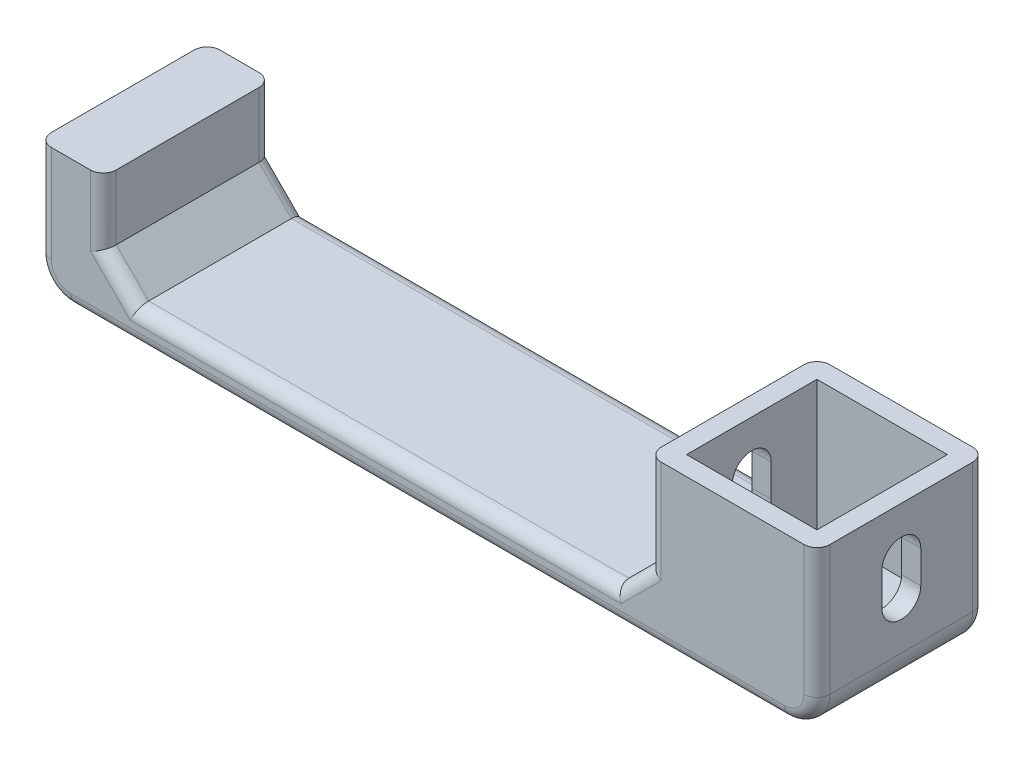
SolidWorks part; units mm, degrees
ref_plane "Front Plane" through (0, 0, 0) normal (0, 0, 1) x (1, 0, 0)
ref_plane "Top Plane" through (0, 0, 0) normal (0, 1, 0) x (1, 0, 0)
ref_plane "Right Plane" through (0, 0, 0) normal (1, 0, 0) x (0, 0, -1)
sketch "Sketch1" plane through (0, 0, 0) normal (0, 1, 0) x (1, 0, 0)
  line L1 (60, -13) -> (-60, -13)
  line L2 (60, -13) -> (60, 13)
  line L3 (60, 13) -> (-60, 13)
  line L4 (-60, -13) -> (-60, 13)
  line L5 (60, -13) -> (-60, 13) construction
  line L6 (60, 13) -> (-60, -13) construction
  point P0 (0, 0)
  dimension "D1" = 26
  dimension "D2" = 120
extrude "Boss-Extrude1" add sketch "Sketch1" along normal blind 25
sketch "Sketch3" plane through (0, 25, 0) normal (0, 1, 0) x (1, 0, 0)
  line L0 (60, 13) -> (-60, 13) construction
  line L1 (-50, 13) -> (34, 13)
  line L2 (-50, 13) -> (-50, -13)
  line L3 (-50, -13) -> (34, -13)
  line L4 (34, 13) -> (34, -13)
  line L5 (-60, -13) -> (60, -13) construction
  line L6 (60, -13) -> (60, 13) construction
  line L7 (-60, 13) -> (-60, -13) construction
  dimension "D1" = 26
  dimension "D2" = 10
extrude "Cut-Extrude1" cut sketch "Sketch3" against normal blind 20
sketch "Sketch4" plane through (0, 25, 0) normal (0, 1, 0) x (1, 0, 0)
  line L0 (-60, -13) -> (-50, -13) construction
  line L1 (-60, 13) -> (-50, 13)
  line L2 (-60, 13) -> (-60, -13)
  line L3 (-60, -13) -> (-50, -13)
  line L4 (-50, 13) -> (-50, -13)
  line L5 (-50, -13) -> (34, -13) construction
extrude "Cut-Extrude2" cut sketch "Sketch4" against normal blind 5
chamfer "Chamfer1" distance 5 angle 45 2 edges at (-50, 5, 0) (34, 5, 0)
sketch "Sketch5" plane through (0, 25, 0) normal (0, 1, 0) x (1, 0, 0)
  line L0 (60, 13) -> (34, 13) construction
  line L1 (36.95, 10.05) -> (57.05, 10.05)
  line L2 (36.95, 10.05) -> (36.95, -10.05)
  line L3 (36.95, -10.05) -> (57.05, -10.05)
  line L4 (57.05, 10.05) -> (57.05, -10.05)
  line L5 (34, -13) -> (60, -13) construction
  line L6 (60, -13) -> (60, 13) construction
  line L7 (34, 13) -> (34, -13) construction
  dimension "D1" = 2.95
  dimension "D2" = 2.95
  dimension "D3" = 2.95
  dimension "D4" = 2.95
extrude "Cut-Extrude3" cut sketch "Sketch5" against normal blind 20
fillet "Fillet1" radius 5 2 edges at (60, 0, 0) (-60, 0, 0)
fillet "Fillet2" radius 2 20 edges at (-60, 12.5, 13) (-58.5355, 1.4645, 13) (60, 15, 13) (58.5355, 1.4645, 13) (60, 15, -13) (58.5355, 1.4645, -13) (-60, 12.5, -13) (-58.5355, 1.4645, -13) (-8, 5, -13) (-47.5, 7.5, -13) (-50, 15, -13) (-50, 15, 13) (-47.5, 7.5, 13) (-8, 5, 13) (31.5, 7.5, 13) (31.5, 7.5, -13) (34, 17.5, 13) (34, 17.5, -13) (0, 0, 13) (0, 0, -13)
sketch "Sketch6" plane through (60, 0, 0) normal (1, 0, 0) x (0, 0, -1)
  line L0 (0, 17.5) -> (0, 12.5) construction
  line L1 (3, 17.5) -> (3, 12.5)
  line L2 (-3, 17.5) -> (-3, 12.5)
  line L3 (13, 25) -> (13, 5) construction
  line L4 (-11, 25) -> (11, 25) construction
  arc A0 (3, 17.5) -> (-3, 17.5) centre (0, 17.5) ccw
  arc A1 (-3, 12.5) -> (3, 12.5) centre (0, 12.5) ccw
  point P2 (0, 15)
  dimension "D2" = 3
  dimension "D1" = 13
  dimension "D3" = 5
  dimension "D4" = 10
extrude "Cut-Extrude4" cut sketch "Sketch6" against normal blind 30
